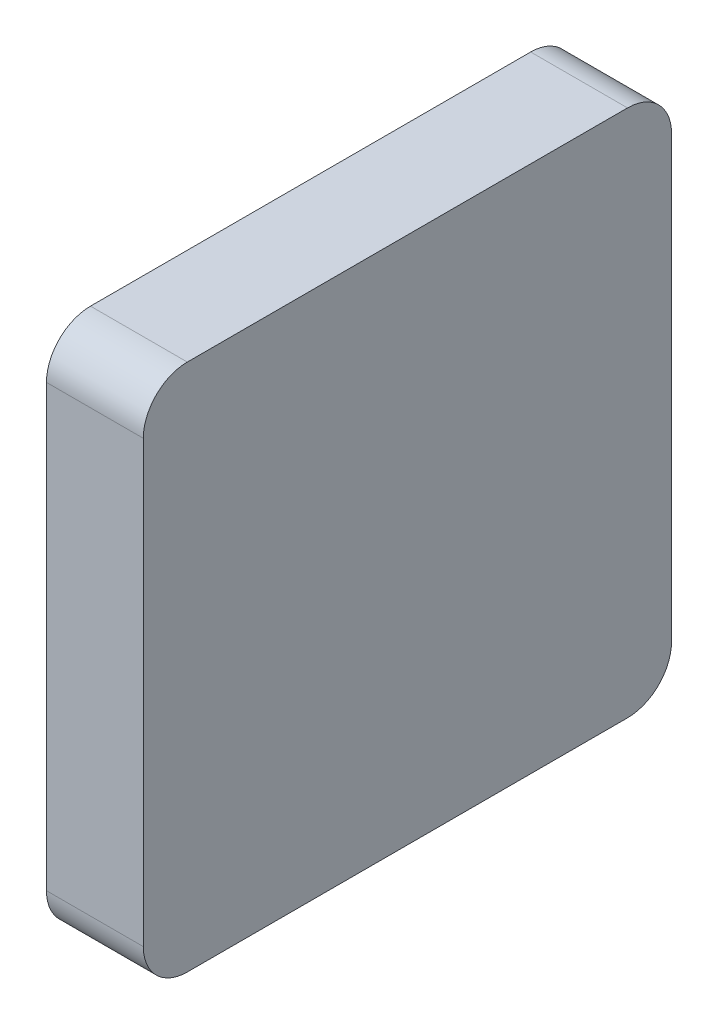
SolidWorks part; units mm, degrees
ref_plane "前视基准面" through (0, 0, 0) normal (0, 0, 1) x (1, 0, 0)
ref_plane "上视基准面" through (0, 0, 0) normal (0, 1, 0) x (1, 0, 0)
ref_plane "右视基准面" through (0, 0, 0) normal (1, 0, 0) x (0, 0, -1)
other "Configuration Table"
sketch "草图1" plane through (0, 0, 0) normal (1, 0, 0) x (0, 0, -1)
  line L1 (-60, 60) -> (60, 60)
  line L2 (-60, 60) -> (-60, -60)
  line L3 (-60, -60) -> (60, -60)
  line L4 (60, 60) -> (60, -60)
  dimension "D1" = 120
  dimension "D2" = 120
  dimension "D3" = 60
  dimension "D4" = 60
extrude "凸台-拉伸1" add sketch "草图1" along normal blind 22
fillet "圆角1" radius 10 4 edges at (11, -60, -60) (11, -60, 60) (11, 60, -60) (11, 60, 60)
